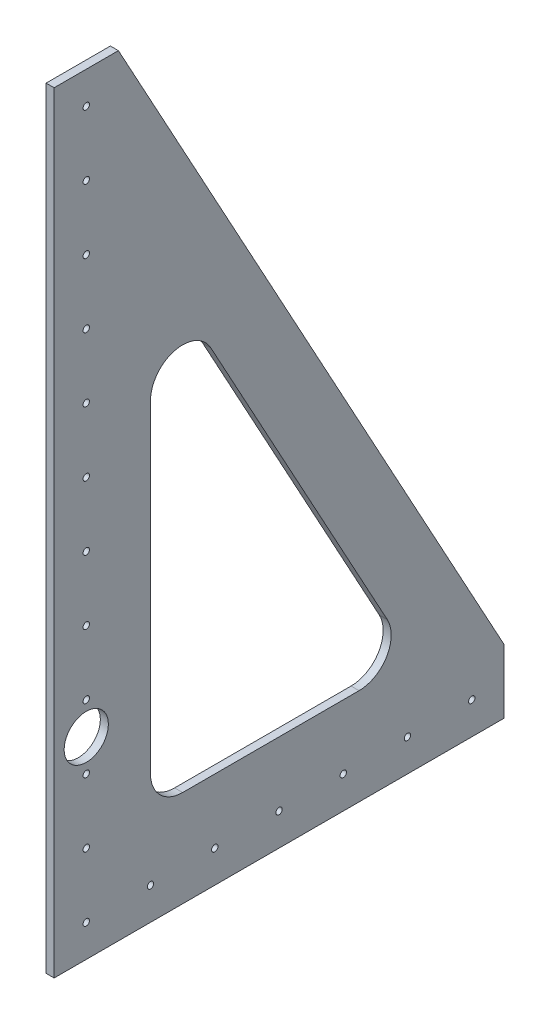
SolidWorks part; units mm, degrees
ref_plane "Front Plane" through (0, 0, 0) normal (0, 0, 1) x (1, 0, 0)
ref_plane "Top Plane" through (0, 0, 0) normal (0, 1, 0) x (1, 0, 0)
ref_plane "Right Plane" through (0, 0, 0) normal (1, 0, 0) x (0, 0, -1)
sketch "Sketch1" plane through (0, 0, 0) normal (1, 0, 0) x (0, 0, -1)
  line L0 (0, 0) -> (0, 609.6)
  line L1 (0, 609.6) -> (50.8, 609.6)
  line L2 (50.8, 609.6) -> (355.6, 50.8)
  line L3 (355.6, 50.8) -> (355.6, 0)
  line L4 (355.6, 0) -> (0, 0)
  line L5 (76.2, 101.6) -> (76.2, 357.3361)
  line L6 (123.8985, 369.499) -> (263.391, 113.7628)
  line L7 (241.0924, 76.2) -> (101.6, 76.2)
  arc A0 (263.391, 113.7628) -> (241.0924, 76.2) centre (241.0924, 101.6) cw
  arc A1 (101.6, 76.2) -> (76.2, 101.6) centre (101.6, 101.6) cw
  arc A2 (123.8985, 369.499) -> (76.2, 357.3361) centre (101.6, 357.3361) ccw
  point P8 (88.7859, 103.3298)
  dimension "D8" = 25.4
  dimension "D1" = 355.6
  dimension "D2" = 50.8
  dimension "D3" = 50.8
  dimension "D4" = 609.6
  dimension "D5" = 25.4
  dimension "D6" = 25.4
  dimension "D7" = 50.8
extrude "Boss-Extrude1" add sketch "Sketch1" along normal blind 6.35
sketch "Sketch2" plane through (6.35, 0, 0) normal (1, 0, 0) x (0, 0, -1)
  line L0 (0, 609.6) -> (0, 0) construction
  line L1 (0, 0) -> (355.6, 0) construction
  circle A0 centre (25.4, 152.4) radius 17.4625
  circle A1 centre (25.4, 25.4) radius 2.54
  circle A38 centre (76.2, 25.4) radius 2.54
  circle A39 centre (127, 25.4) radius 2.54
  circle A40 centre (177.8, 25.4) radius 2.54
  circle A41 centre (228.6, 25.4) radius 2.54
  circle A42 centre (279.4, 25.4) radius 2.54
  circle A56 centre (25.4, 76.2) radius 2.54
  circle A57 centre (330.2, 25.4) radius 2.54
  circle A58 centre (25.4, 127) radius 2.54
  circle A59 centre (25.4, 177.8) radius 2.54
  circle A60 centre (25.4, 228.6) radius 2.54
  circle A61 centre (25.4, 279.4) radius 2.54
  circle A62 centre (25.4, 330.2) radius 2.54
  circle A63 centre (25.4, 381) radius 2.54
  circle A64 centre (25.4, 431.8) radius 2.54
  circle A65 centre (25.4, 482.6) radius 2.54
  circle A66 centre (25.4, 533.4) radius 2.54
  circle A67 centre (25.4, 584.2) radius 2.54
  dimension "D1" = 34.925
  dimension "D4" = 5.08
  dimension "D2" = 7
  dimension "D3" = 152.4
  dimension "D5" = 25.4
  dimension "1" = 25.4
  dimension "D6" = 12
extrude "Cut-Extrude1" cut sketch "Sketch2" against normal through all
